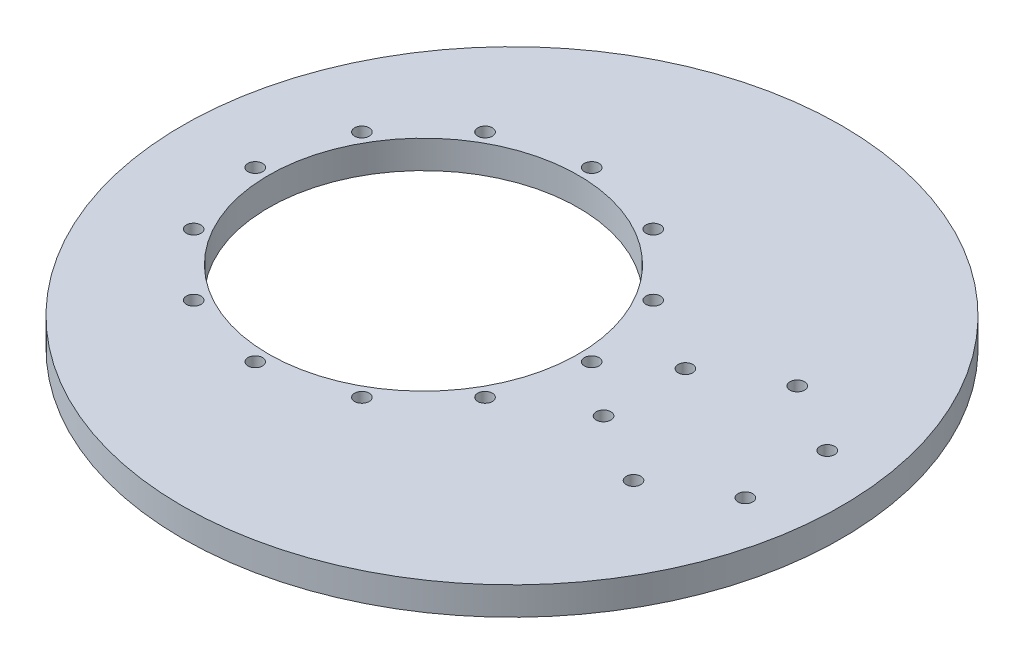
SolidWorks part; units mm, degrees
ref_plane "Front Plane" through (0, 0, 0) normal (0, 0, 1) x (1, 0, 0)
ref_plane "Top Plane" through (0, 0, 0) normal (0, 1, 0) x (1, 0, 0)
ref_plane "Right Plane" through (0, 0, 0) normal (1, 0, 0) x (0, 0, -1)
sketch "Sketch1" plane through (0, 0, 0) normal (0, 1, 0) x (1, 0, 0)
  line L0 (0, 38) -> (0, 0) construction
  line L1 (65.95, 18.5) -> (65.95, 0) construction
  line L2 (0, 0) -> (65.95, 0) construction
  line L3 (65.95, 0) -> (49.9285, -9.25) construction
  line L4 (44.45, 0) -> (47.45, 0) construction
  line L5 (65.95, 0) -> (81.9715, 9.25) construction
  line L6 (65.95, 0) -> (65.95, -18.5) construction
  line L7 (65.95, 0) -> (49.9285, 9.25) construction
  line L8 (65.95, 0) -> (84.45, 0) construction
  line L9 (65.95, 0) -> (81.9715, -9.25) construction
  circle A0 centre (0, 0) radius 38 construction
  circle A1 centre (0, 0) radius 44.45
  circle A2 centre (0, 0) radius 35
  circle A3 centre (65.95, 0) radius 18.5
  circle A4 centre (20, 0) radius 74.45
  point P3 (0, 38)
  point P4 (19, 32.909)
  point P7 (32.909, 19)
  point P8 (38, 0)
  point P9 (32.909, -19)
  point P10 (19, -32.909)
  point P11 (0, -38)
  point P12 (-19, -32.909)
  point P13 (-32.909, -19)
  point P14 (-38, 0)
  point P15 (-32.909, 19)
  point P16 (-19, 32.909)
  point P17 (0, 0)
  point P21 (65.95, 18.5)
  point P34 (-44.45, 0)
  point P35 (-54.45, 0)
  dimension "D1" = 76
  dimension "D3" = 88.9
  dimension "D5" = 37
  dimension "D12" = 148.9
  dimension "D4" = 3
  dimension "D7" = 3
  dimension "D6" = 30
  dimension "D8" = 30
  dimension "D9" = 30
  dimension "D10" = 30
  dimension "D11" = 128.9
  dimension "D13" = 10
  dimension "D2" = 12
extrude "Boss-Extrude1" add sketch "Sketch1" along normal blind 6.35
hole_wizard "M4x0.7 Tapped Hole1" positions "3DSketch2" profile "Sketch3" tap size "M4x0.7" standard "ANSI Metric" end condition through all
sketch3d "3DSketch2"
  point P5 (0, 0, -38)
  point P14 (-19, 0, -32.909)
  point P18 (-32.909, 0, -19)
  point P20 (-38, 0, 0)
  point P26 (-32.909, 0, 19)
  point P28 (-19, 0, 32.909)
  point P30 (0, 0, 38)
  point P39 (19, 0, 32.909)
  point P41 (32.909, 0, 19)
  point P43 (38, 0, 0)
  point P53 (19, 0, -32.909)
  point P55 (32.909, 0, -19)
  point P65 (65.95, 6.35, -18.5)
  point P67 (81.9715, 6.35, -9.25)
  point P69 (81.9715, 6.35, 9.25)
  point P71 (65.95, 6.35, 18.5)
  point P73 (49.9285, 6.35, 9.25)
  point P75 (49.9285, 6.35, -9.25)
  point P79 (0, 0, 0)
  point P81 (0, 0, 0)
  point P83 (0, 0, 0)
  point P85 (0, 0, 0)
  point P87 (0, 0, 0)
sketch "Sketch3" plane through (0, 0, -38) normal (1, 0, 0) x (0, 0, -1)
  line L0 (0, 0) -> (0, 6.35)
  line L1 (0, 6.35) -> (1.65, 6.35)
  line L2 (1.65, 6.35) -> (1.65, 0)
  line L5 (1.65, 0) -> (0, 0)
  line L11 (0, -6.35) -> (0, 107.95) construction
  dimension "Thru Tap Drill Dia." = 3.3
  dimension "Thru Tap Drill Depth" = 6.35
cosmetic thread "Hole Thread13" parameters "D2"=4
cosmetic thread "Hole Thread14" parameters "D2"=4
cosmetic thread "Hole Thread15" parameters "D2"=4
cosmetic thread "Hole Thread16" parameters "D2"=4
cosmetic thread "Hole Thread17" parameters "D2"=4
cosmetic thread "Hole Thread18" parameters "D2"=4
cosmetic thread "Hole Thread19" parameters "D2"=4
cosmetic thread "Hole Thread20" parameters "D2"=4
cosmetic thread "Hole Thread21" parameters "D2"=4
cosmetic thread "Hole Thread22" parameters "D2"=4
cosmetic thread "Hole Thread23" parameters "D2"=4
cosmetic thread "Hole Thread24" parameters "D2"=4
cosmetic thread "Hole Thread25" parameters "D2"=4
cosmetic thread "Hole Thread26" parameters "D2"=4
cosmetic thread "Hole Thread27" parameters "D2"=4
cosmetic thread "Hole Thread28" parameters "D2"=4
cosmetic thread "Hole Thread29" parameters "D2"=4
cosmetic thread "Hole Thread30" parameters "D2"=4
equation "\"D8@Sketch1\"=\"D6@Sketch1\""
equation "\"D9@Sketch1\"=\"D8@Sketch1\""
equation "\"D10@Sketch1\"=\"D8@Sketch1\""
equation "\"D12@Sketch1\"=\"D11@Sketch1\"+20"
equation "\"D13@Sketch1\"=(\"D12@Sketch1\"-\"D11@Sketch1\")/2"
